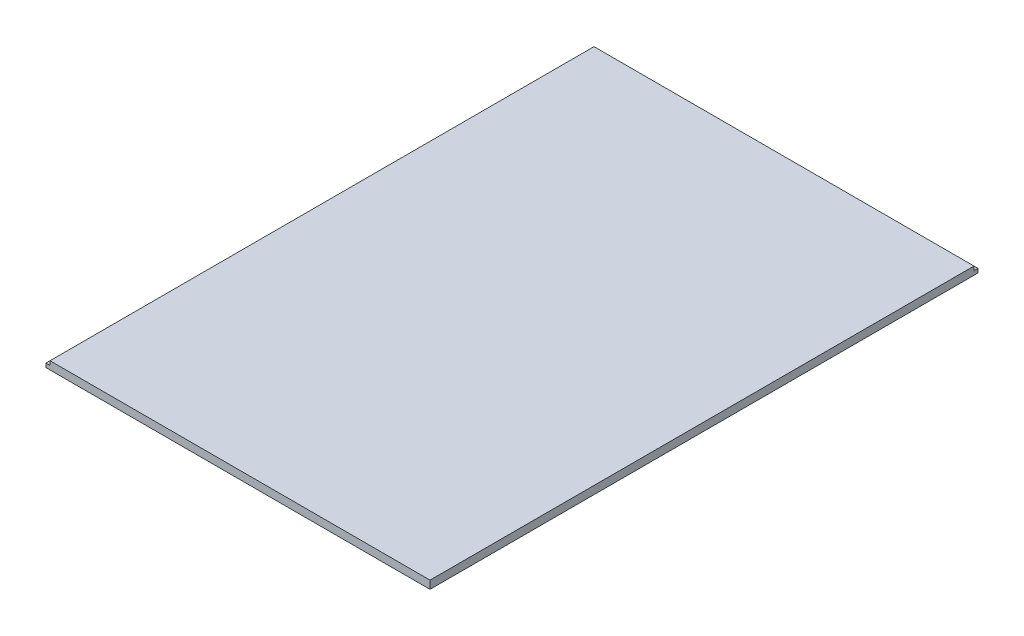
SolidWorks part; units mm, degrees
material "Perspex (TM) GS Acrylic Cast Sheet"
ref_plane "Front Plane" through (0, 0, 0) normal (0, 0, 1) x (1, 0, 0)
ref_plane "Top Plane" through (0, 0, 0) normal (0, 1, 0) x (1, 0, 0)
ref_plane "Right Plane" through (0, 0, 0) normal (1, 0, 0) x (0, 0, -1)
sketch "Sketch1" plane through (0, 0, 0) normal (0, 1, 0) x (1, 0, 0)
  line L1 (0, 0) -> (304.8, 0)
  line L2 (0, 0) -> (0, 434.975)
  line L3 (0, 434.975) -> (304.8, 434.975)
  line L4 (304.8, 0) -> (304.8, 434.975)
  dimension "D1" = 304.8
  dimension "D2" = 434.975
extrude "Boss-Extrude1" add sketch "Sketch1" along normal blind 6.35
sketch "Sketch2" plane through (0, 6.35, 0) normal (0, 1, 0) x (1, 0, 0)
  line L0 (3.175, 0) -> (3.175, 431.8)
  line L1 (3.175, 431.8) -> (304.8, 431.8)
  line L2 (3.175, 431.8) -> (0, 431.8) construction
  line L3 (3.175, 431.8) -> (3.175, 434.975) construction
  line L4 (0, 434.975) -> (0, 0)
  line L5 (0, 0) -> (304.8, 0)
  line L6 (304.8, 0) -> (304.8, 434.975)
  line L7 (304.8, 434.975) -> (0, 434.975)
  line L8 (0, 434.975) -> (0, 0) construction
  line L9 (0, 0) -> (304.8, 0) construction
  line L10 (304.8, 0) -> (304.8, 434.975) construction
  line L11 (304.8, 434.975) -> (0, 434.975) construction
  line L12 (3.175, 0) -> (0, 0)
  line L13 (0, 0) -> (0, 434.975)
  line L14 (0, 434.975) -> (304.8, 434.975)
  line L15 (304.8, 434.975) -> (304.8, 431.8)
  dimension "D2" = 3.175
  dimension "D1" = 0
extrude "Cut-Extrude1" cut sketch "Sketch2" against normal blind 3.175
